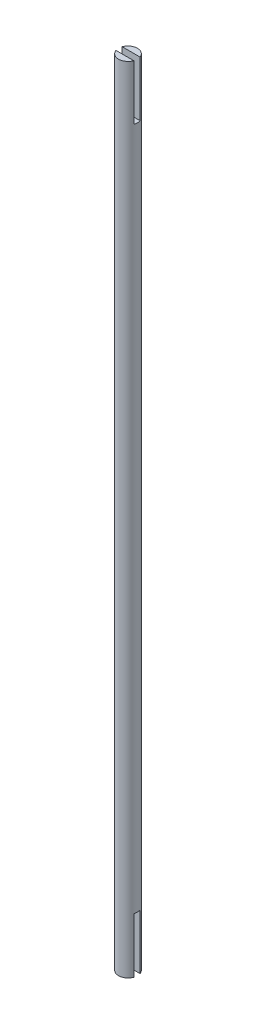
SolidWorks part; units mm, degrees
ref_plane "Front Plane" through (0, 0, 0) normal (0, 0, 1) x (1, 0, 0)
ref_plane "Top Plane" through (0, 0, 0) normal (0, 1, 0) x (1, 0, 0)
ref_plane "Right Plane" through (0, 0, 0) normal (1, 0, 0) x (0, 0, -1)
sketch "Sketch1" plane through (0, 0, 0) normal (0, 1, 0) x (1, 0, 0)
  circle A0 centre (0, 0) radius 3
  dimension "D1" = 6
extrude "Boss-Extrude1" add sketch "Sketch1" along normal blind 252
sketch "Sketch2" plane through (0, 0, 0) normal (1, 0, 0) x (0, 0, -1)
  line L0 (-3, 0) -> (3, 0) construction
  line L1 (-1, 0) -> (1, 0)
  line L2 (-1, 0) -> (-1, 17.5)
  line L3 (-1, 17.5) -> (1, 17.5)
  line L4 (1, 0) -> (1, 17.5)
  line L5 (-12.3681, 17.5) -> (12.5004, 17.5) construction
  line L6 (3, 0) -> (3, 252) construction
  line L13 (3, 252) -> (-3, 252) construction
  line L14 (-1, 252) -> (1, 252)
  line L15 (-1, 252) -> (-1, 234.5)
  line L16 (-1, 234.5) -> (1, 234.5)
  line L17 (1, 252) -> (1, 234.5)
  line L18 (3, 0) -> (3, 252) construction
  dimension "D1" = 2
  dimension "D2" = 2
  dimension "D3" = 17.5
  dimension "D4" = 2
  dimension "D5" = 2
extrude "Cut-Extrude2" cut sketch "Sketch2" against normal through all both and the other way through all contours L17 L14 L15 L16 | L1 L4 L3 L2
